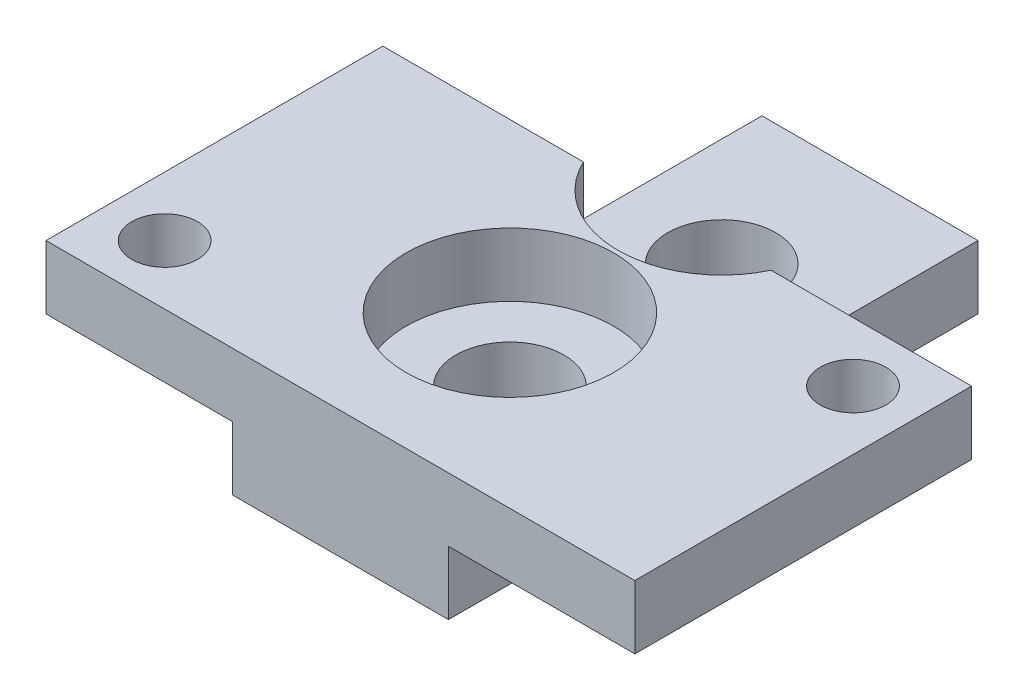
SolidWorks part; units mm, degrees
ref_plane "Front Plane" through (0, 0, 0) normal (0, 0, 1) x (1, 0, 0)
ref_plane "Top Plane" through (0, 0, 0) normal (0, 1, 0) x (1, 0, 0)
ref_plane "Right Plane" through (0, 0, 0) normal (1, 0, 0) x (0, 0, -1)
sketch "Sketch1" plane through (0, 0, 0) normal (0, 1, 0) x (1, 0, 0)
  line L1 (0, 0) -> (27.8, 0)
  line L2 (0, 0) -> (0, 15.9)
  line L3 (0, 15.9) -> (27.8, 15.9)
  line L4 (27.8, 0) -> (27.8, 15.9)
  circle A0 centre (2.8, 2.8) radius 1.55
  circle A1 centre (25, 13.1) radius 1.55
  dimension "D3" = 3.1
  dimension "D1" = 27.8
  dimension "D2" = 15.9
  dimension "D4" = 2.8
  dimension "D5" = 2.8
  dimension "D6" = 2.8
  dimension "D7" = 2.8
extrude "Boss-Extrude1" add sketch "Sketch1" along normal blind 3
sketch "Sketch2" plane through (0, 0, 0) normal (0, -1, 0) x (1, 0, 0)
  line L0 (0, 0) -> (27.8, 0) construction
  line L1 (8.8, 0) -> (19, 0)
  line L2 (8.8, 0) -> (8.8, -25)
  line L3 (8.8, -25) -> (19, -25)
  line L4 (19, 0) -> (19, -25)
  circle A0 centre (2.8, -2.8) radius 1.55 construction
  circle A1 centre (25, -13.1) radius 1.55 construction
  dimension "D1" = 6
  dimension "D2" = 6
  dimension "D3" = 25
extrude "Boss-Extrude2" add sketch "Sketch2" along normal blind 3
sketch "Sketch3" plane through (0, -3, 0) normal (0, -1, 0) x (1, 0, 0)
  line L0 (19, 0) -> (8.8, 0) construction
  line L1 (13.9, -8) -> (13.9, -18) construction
  line L2 (8.8, 0) -> (8.8, -25) construction
  line L3 (19, -25) -> (19, 0) construction
  circle A0 centre (13.9, -8) radius 2.55
  circle A1 centre (13.9, -18) radius 2.55
  dimension "D1" = 5.1
  dimension "D2" = 8
  dimension "D3" = 10
extrude "Cut-Extrude1" cut sketch "Sketch3" against normal blind 3
sketch "Sketch4" plane through (0, 3, 0) normal (0, 1, 0) x (1, 0, 0)
  circle A0 centre (13.9, 8) radius 2.55 construction
  arc A1 (15.3465, 15.9) -> (12.4535, 15.9) centre (13.9, 18) ccw construction
  circle A2 centre (13.9, 8) radius 2.55
  arc A3 (15.3465, 15.9) -> (12.4535, 15.9) centre (13.9, 18) ccw
  circle A4 centre (13.9, 18) radius 4.9
  circle A5 centre (13.9, 8) radius 4.9
  line M7 (27.8, 15.9) -> (0, 15.9)
  dimension "D1" = 9.8
extrude "Cut-Extrude4" cut sketch "Sketch4" against normal blind 3 contours A4 M7 | A5 A2 | A2
